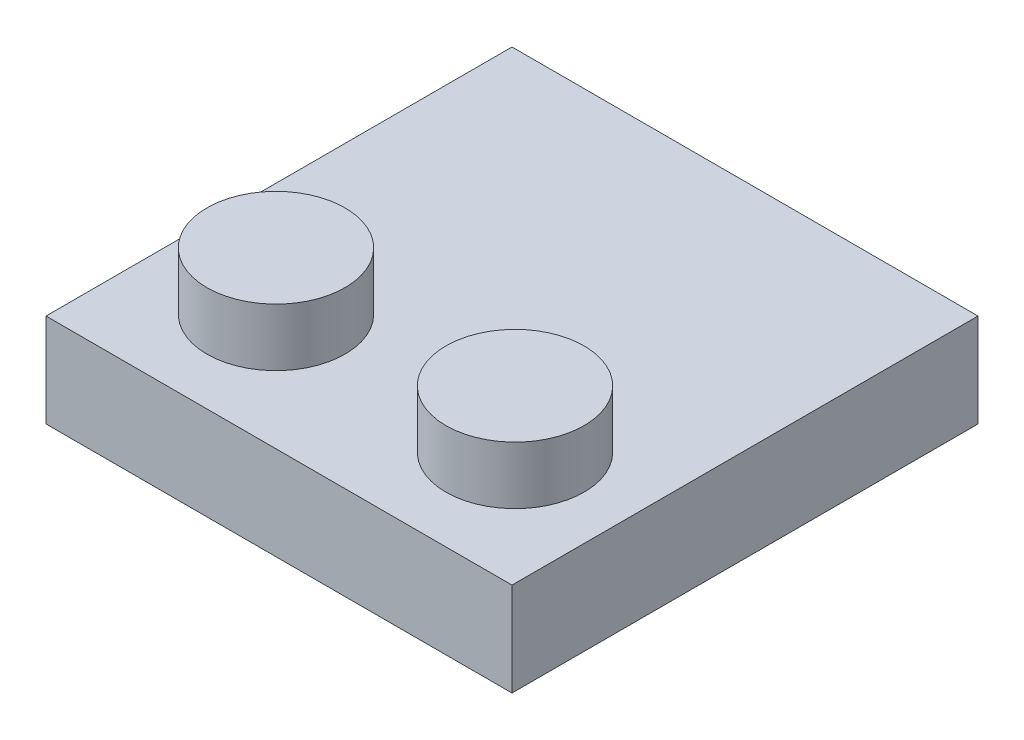
SolidWorks part; units mm, degrees
ref_plane "Front Plane" through (0, 0, 0) normal (0, 0, 1) x (1, 0, 0)
ref_plane "Top Plane" through (0, 0, 0) normal (0, 1, 0) x (1, 0, 0)
ref_plane "Right Plane" through (0, 0, 0) normal (1, 0, 0) x (0, 0, -1)
sketch "Sketch1" plane through (0, 0, 0) normal (0, 1, 0) x (1, 0, 0)
  line L1 (-7.925, 7.925) -> (7.925, 7.925)
  line L2 (-7.925, 7.925) -> (-7.925, -7.925)
  line L3 (-7.925, -7.925) -> (7.925, -7.925)
  line L4 (7.925, 7.925) -> (7.925, -7.925)
  line L5 (-7.925, 7.925) -> (7.925, -7.925) construction
  line L6 (-7.925, -7.925) -> (7.925, 7.925) construction
  point P0 (0, 0)
  dimension "D1" = 15.85
  dimension "D2" = 15.85
extrude "Boss-Extrude1" add sketch "Sketch1" against normal blind 3.18
sketch "Sketch2" plane through (0, 0, 0) normal (0, 1, 0) x (1, 0, 0)
  line L0 (-7.925, -7.925) -> (7.925, -7.925) construction
  line L2 (7.925, -7.925) -> (7.925, 7.925) construction
  line L3 (-7.925, 7.925) -> (-7.925, -7.925) construction
  circle A0 centre (-4.065, -3.9625) radius 2.35
  circle A1 centre (4.0652, -3.9625) radius 2.35
  dimension "D1" = 3.86
  dimension "D2" = 3.9625
  dimension "D3" = 3.9625
  dimension "D4" = 4.7
  dimension "D5" = 4.7
  dimension "D6" = 3.8598
extrude "Boss-Extrude2" add sketch "Sketch2" along normal blind 1.96
shell "Shell1" thickness 1.38
sketch "Sketch3" plane through (0, -1.38, 0) normal (0, -1, 0) x (1, 0, 0)
  circle A0 centre (0, 0) radius 3.1
  circle A1 centre (0, 0) radius 2.82
  dimension "D1" = 6.2
  dimension "D2" = 5.64
extrude "Boss-Extrude3" add sketch "Sketch3" along normal blind 1.48
